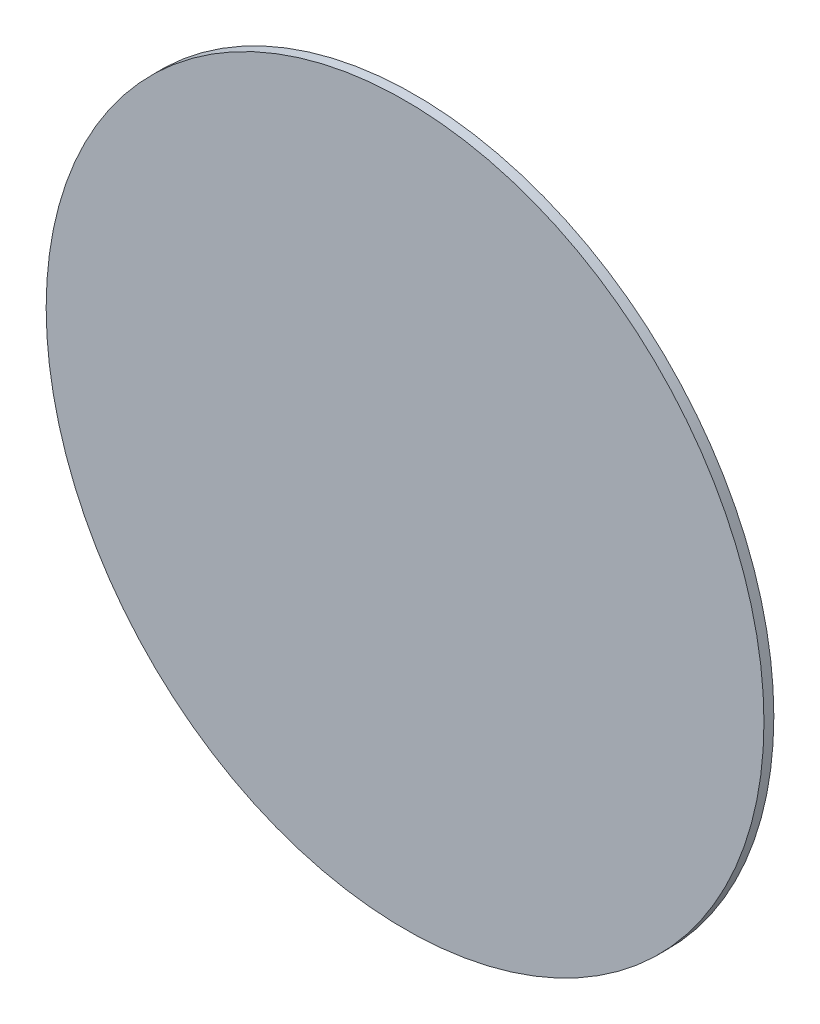
SolidWorks part; units mm, degrees
material "PMMA"
ref_plane "Plan de face" through (0, 0, 0) normal (0, 0, 1) x (1, 0, 0)
ref_plane "Plan de dessus" through (0, 0, 0) normal (0, 1, 0) x (1, 0, 0)
ref_plane "Plan de droite" through (0, 0, 0) normal (1, 0, 0) x (0, 0, -1)
sketch "Esquisse1" plane through (0, 0, 0) normal (0, 0, 1) x (1, 0, 0)
  circle A0 centre (0, 0) radius 363.2
  dimension "D1" = 726.4
extrude "Boss.-Extru.1" add sketch "Esquisse1" along normal blind 10
